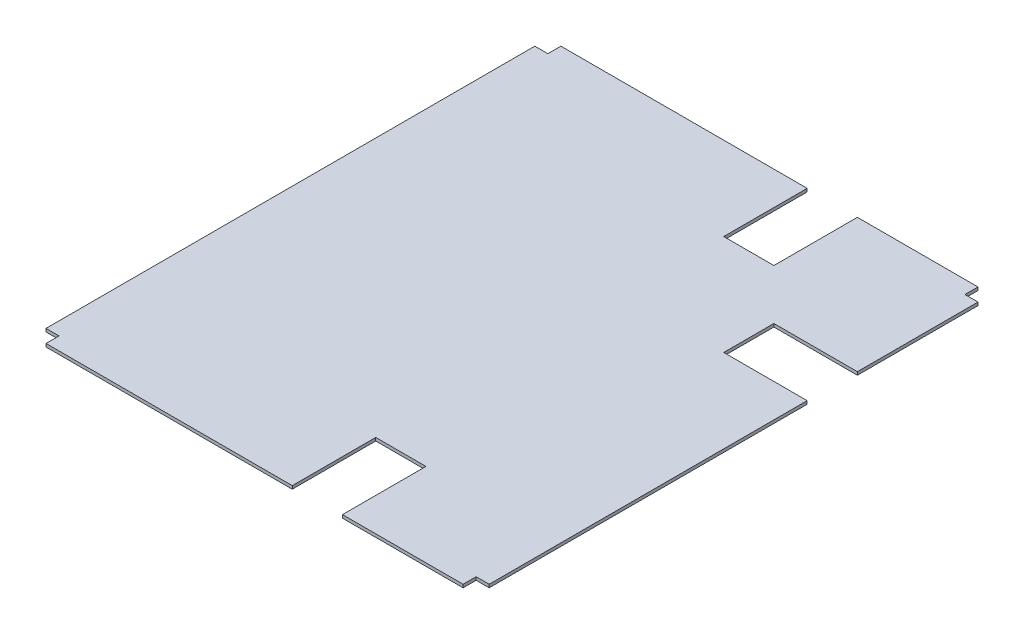
SolidWorks part; units mm, degrees
ref_plane "Front Plane" through (0, 0, 0) normal (0, 0, 1) x (1, 0, 0)
ref_plane "Top Plane" through (0, 0, 0) normal (0, 1, 0) x (1, 0, 0)
ref_plane "Right Plane" through (0, 0, 0) normal (1, 0, 0) x (0, 0, -1)
sketch "Sketch1" plane through (0, 0, 0) normal (0, 1, 0) x (1, 0, 0)
  line L0 (-1545, 1213) -> (963, 1213) construction
  line L1 (-1545, -1795) -> (1545, -1795) construction
  line L2 (-1545, -1795) -> (-1545, -1) construction
  line L3 (-1545, 1795) -> (1545, 1795) construction
  line L4 (1545, -1795) -> (1545, 1795) construction
  line L5 (-1545, -1795) -> (1545, 1795) construction
  line L6 (-1545, 1795) -> (1545, -1795) construction
  line L7 (963, 1213) -> (963, -1213) construction
  line L8 (963, -1213) -> (-200, -1213) construction
  line L9 (-200, -1213) -> (-200, -1795) construction
  line L10 (-200, -1795) -> (-516, -1795)
  line L11 (-1454, -1795) -> (-1454, -1704)
  line L12 (-1454, -1704) -> (-1545, -1704)
  line L13 (-1545, -1704) -> (-1545, -1)
  line L14 (-1545, 1213) -> (-1545, 1704)
  line L15 (-1545, 1704) -> (-1454, 1704)
  line L16 (-1454, 1704) -> (-1454, 1795)
  line L17 (-1454, 1795) -> (-516, 1795)
  line L18 (263, 1795) -> (263, 1213)
  line L19 (263, 1213) -> (516, 1213)
  line L20 (613, 1213) -> (613, 1795)
  line L21 (613, 1795) -> (1454, 1795)
  line L22 (1454, 1795) -> (1454, 1704)
  line L23 (1454, 1704) -> (1545, 1704)
  line L24 (1545, 1704) -> (1545, 863)
  line L25 (1545, 863) -> (963, 863)
  line L26 (963, 863) -> (963, 513)
  line L27 (963, 513) -> (1545, 513)
  line L28 (1545, 513) -> (1545, -1)
  line L29 (1545, -1704) -> (1454, -1704)
  line L30 (1454, -1704) -> (1454, -1795)
  line L31 (1454, -1795) -> (613, -1795)
  line L32 (613, -1795) -> (613, -1213)
  line L33 (613, -1213) -> (514, -1213)
  line L34 (263, -1213) -> (263, -1795)
  line L35 (263, -1795) -> (-200, -1795)
  line L45 (-1545, -1) -> (-1545, 1213)
  line L60 (1545, -1) -> (1545, -1704)
  line L61 (514, -1213) -> (263, -1213)
  line L62 (-516, -1795) -> (-1454, -1795)
  line L63 (-516, 1795) -> (263, 1795)
  line L64 (516, 1213) -> (613, 1213)
  line L65 (-1545, -1) -> (-1545, 1795) construction
  point P0 (0, 0)
  dimension "D1" = 3590
  dimension "D2" = 3090
  dimension "D3" = 582
  dimension "D4" = 582
  dimension "D5" = 582
  dimension "D6" = 200
  dimension "D7" = 91
  dimension "D8" = 91
  dimension "D9" = 350
  dimension "D10" = 350
  dimension "D11" = 350
  dimension "D12" = 350
  dimension "D20" = 350
  dimension "D21" = 350
extrude "Boss-Extrude1" add sketch "Sketch1" along normal blind 21.7
equation "\"D3@Sketch1\" = 600 - 18"
equation "\"D4@Sketch1\"=\"D3@Sketch1\""
equation "\"D5@Sketch1\"=\"D4@Sketch1\""
equation "\"D7@Sketch1\"=\"D8@Sketch1\""
equation "\"D11@Sketch1\"=\"D10@Sketch1\""
equation "\"D12@Sketch1\"=\"D11@Sketch1\""
equation "\"D15@Sketch1\"=\"D14@Sketch1\""
